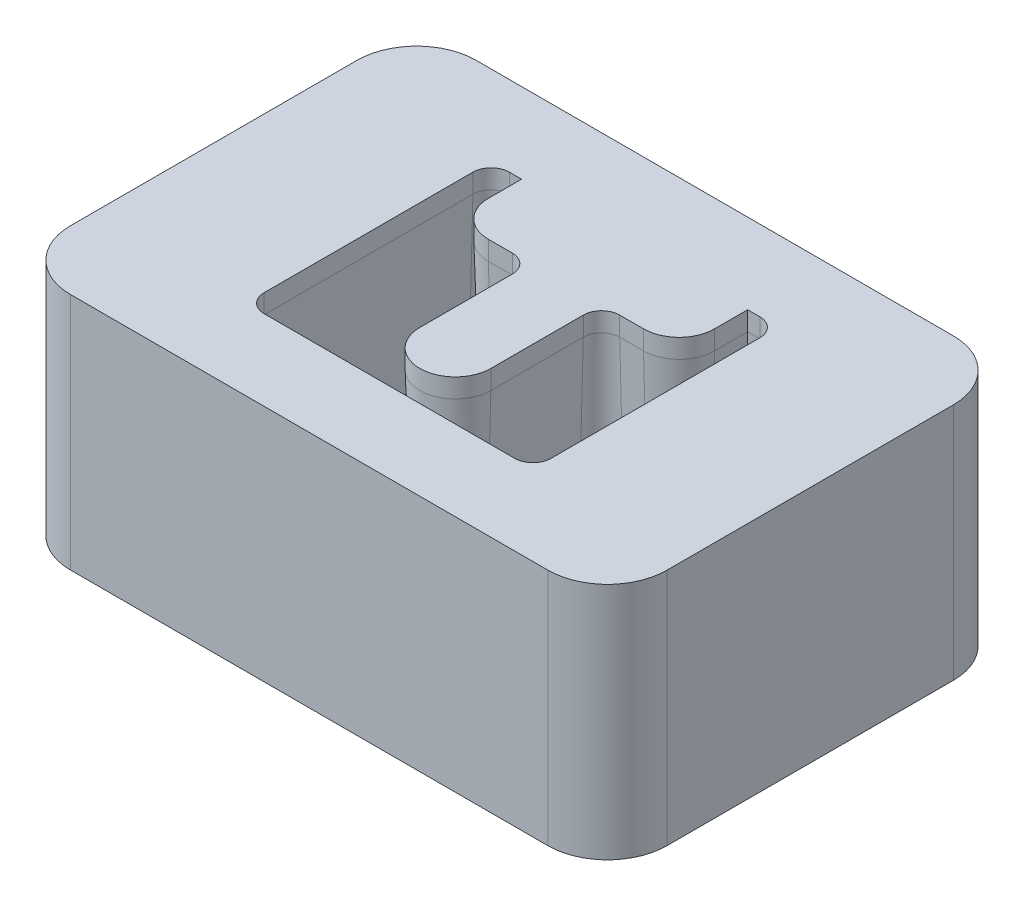
SolidWorks part; units mm, degrees
material "K110"
ref_plane "Front Plane" through (0, 0, 0) normal (0, 0, 1) x (1, 0, 0)
ref_plane "Top Plane" through (0, 0, 0) normal (0, 1, 0) x (1, 0, 0)
ref_plane "Right Plane" through (0, 0, 0) normal (1, 0, 0) x (0, 0, -1)
sketch "Sketch1" plane through (0, 0, 0) normal (0, 1, 0) x (1, 0, 0)
  line L1 (-50, -34) -> (50, -34)
  line L2 (-50, -34) -> (-50, 34)
  line L3 (-50, 34) -> (50, 34)
  line L4 (50, -34) -> (50, 34)
  line L5 (-50, -34) -> (50, 34) construction
  line L6 (-50, 34) -> (50, -34) construction
  point P0 (0, 0)
  dimension "D1" = 68
  dimension "D2" = 100
extrude "Boss-Extrude1" add sketch "Sketch1" against normal blind 40
fillet "Fillet1" radius 10 4 edges at (-50, -20, -34) (50, -20, -34) (50, -20, 34) (-50, -20, 34)
sketch "Sketch2" plane through (0, 0, 0) normal (0, 1, 0) x (1, 0, 0)
  line L22 (-21, -20.55) -> (21, -20.55)
  line L23 (-24.05, 17.5) -> (-24.05, -17.5)
  line L24 (-18.95, 20.55) -> (-21, 20.55)
  line L25 (-18.95, 15) -> (-18.95, 20.55)
  line L26 (-9, 9.05) -> (-13, 9.05)
  line L27 (-5.95, -9.5) -> (-5.95, 6)
  line L28 (5.95, 6) -> (5.95, -9.5)
  line L29 (13, 9.05) -> (9, 9.05)
  line L30 (18.95, 20.55) -> (18.95, 15)
  line L31 (21, 20.55) -> (18.95, 20.55)
  line L32 (24.05, -17.5) -> (24.05, 17.5)
  line L33 (-21, -20.55) -> (21, -20.55)
  line L34 (-24.05, 17.5) -> (-24.05, -17.5)
  line L35 (-18.95, 20.55) -> (-21, 20.55)
  line L36 (-18.95, 15) -> (-18.95, 20.55)
  line L37 (-9, 9.05) -> (-13, 9.05)
  line L38 (-5.95, -9.5) -> (-5.95, 6)
  line L39 (5.95, 6) -> (5.95, -9.5)
  line L40 (13, 9.05) -> (9, 9.05)
  line L41 (18.95, 20.55) -> (18.95, 15)
  line L42 (21, 20.55) -> (18.95, 20.55)
  line L43 (24.05, -17.5) -> (24.05, 17.5)
  arc A18 (21, -20.55) -> (24.05, -17.5) centre (21, -17.5) ccw
  arc A19 (-24.05, -17.5) -> (-21, -20.55) centre (-21, -17.5) ccw
  arc A20 (-21, 20.55) -> (-24.05, 17.5) centre (-21, 17.5) ccw
  arc A21 (-18.95, 15) -> (-13, 9.05) centre (-13, 15) ccw
  arc A22 (-5.95, 6) -> (-9, 9.05) centre (-9, 6) ccw
  arc A23 (-5.95, -9.5) -> (5.95, -9.5) centre (0, -9.5) ccw
  arc A24 (9, 9.05) -> (5.95, 6) centre (9, 6) ccw
  arc A25 (13, 9.05) -> (18.95, 15) centre (13, 15) ccw
  arc A26 (24.05, 17.5) -> (21, 20.55) centre (21, 17.5) ccw
  arc A27 (21, -20.55) -> (24.05, -17.5) centre (21, -17.5) ccw
  arc A28 (-24.05, -17.5) -> (-21, -20.55) centre (-21, -17.5) ccw
  arc A29 (-21, 20.55) -> (-24.05, 17.5) centre (-21, 17.5) ccw
  arc A30 (-18.95, 15) -> (-13, 9.05) centre (-13, 15) ccw
  arc A31 (-5.95, 6) -> (-9, 9.05) centre (-9, 6) ccw
  arc A32 (-5.95, -9.5) -> (5.95, -9.5) centre (0, -9.5) ccw
  arc A33 (9, 9.05) -> (5.95, 6) centre (9, 6) ccw
  arc A34 (13, 9.05) -> (18.95, 15) centre (13, 15) ccw
  arc A35 (24.05, 17.5) -> (21, 20.55) centre (21, 17.5) ccw
  dimension "D1" = 0.05
extrude "Cut-Extrude1" cut sketch "Sketch2" against normal up to next
sketch "Sketch3" plane through (0, 0, 0) normal (0, 0, 1) x (1, 0, 0)
  line L6 (24.05, -3.2) -> (25.0136, -40)
  line L7 (40, -40) -> (40, 0) construction
  line L8 (40, -40) -> (50, -40) construction
  line L11 (37.4, 0) -> (-37.4, 0) construction
  line L12 (25.0136, -40) -> (23.05, -40)
  line L13 (-40, -40) -> (40, -40) construction
  line L14 (23.05, -3.2) -> (24.05, -3.2)
  line L15 (23.05, -40) -> (23.05, -3.2)
  line L16 (24.05, -40) -> (24.05, 0) construction
  dimension "D1" = 3.2
  dimension "D2" = 1.5
  dimension "D3" = 1
sketch "Sketch5" plane through (0, 0, 0) normal (0, 1, 0) x (1, 0, 0)
  line L0 (21, 20.55) -> (18.95, 20.55) construction
  line L1 (24.05, -17.5) -> (24.05, 17.5) construction
  line L2 (18.95, 20.55) -> (18.95, 15) construction
  line L3 (13, 9.05) -> (9, 9.05) construction
  line L4 (5.95, 6) -> (5.95, -9.5) construction
  line L5 (-5.95, -9.5) -> (-5.95, 6) construction
  line L6 (-9, 9.05) -> (-13, 9.05) construction
  line L7 (-18.95, 15) -> (-18.95, 20.55) construction
  line L8 (-18.95, 20.55) -> (-21, 20.55) construction
  line L9 (-24.05, 17.5) -> (-24.05, -17.5) construction
  line L10 (-21, -20.55) -> (21, -20.55) construction
  line L11 (-21, -20.55) -> (21, -20.55)
  line L12 (-24.05, 17.5) -> (-24.05, -17.5)
  line L13 (-18.95, 20.55) -> (-21, 20.55)
  line L14 (-18.95, 15) -> (-18.95, 20.55)
  line L15 (-9, 9.05) -> (-13, 9.05)
  line L16 (-5.95, -9.5) -> (-5.95, 6)
  line L17 (5.95, 6) -> (5.95, -9.5)
  line L18 (13, 9.05) -> (9, 9.05)
  line L19 (18.95, 20.55) -> (18.95, 15)
  line L20 (24.05, -17.5) -> (24.05, 17.5)
  line L21 (21, 20.55) -> (18.95, 20.55)
  arc A0 (-5.95, 6) -> (-9, 9.05) centre (-9, 6) ccw construction
  arc A1 (24.05, 17.5) -> (21, 20.55) centre (21, 17.5) ccw construction
  arc A2 (13, 9.05) -> (18.95, 15) centre (13, 15) ccw construction
  arc A3 (9, 9.05) -> (5.95, 6) centre (9, 6) ccw construction
  arc A4 (-5.95, -9.5) -> (5.95, -9.5) centre (0, -9.5) ccw construction
  arc A5 (-18.95, 15) -> (-13, 9.05) centre (-13, 15) ccw construction
  arc A6 (-21, 20.55) -> (-24.05, 17.5) centre (-21, 17.5) ccw construction
  arc A7 (-24.05, -17.5) -> (-21, -20.55) centre (-21, -17.5) ccw construction
  arc A8 (21, -20.55) -> (24.05, -17.5) centre (21, -17.5) ccw construction
  arc A9 (21, -20.55) -> (24.05, -17.5) centre (21, -17.5) ccw
  arc A10 (-24.05, -17.5) -> (-21, -20.55) centre (-21, -17.5) ccw
  arc A11 (-21, 20.55) -> (-24.05, 17.5) centre (-21, 17.5) ccw
  arc A12 (-18.95, 15) -> (-13, 9.05) centre (-13, 15) ccw
  arc A13 (-5.95, 6) -> (-9, 9.05) centre (-9, 6) ccw
  arc A14 (-5.95, -9.5) -> (5.95, -9.5) centre (0, -9.5) ccw
  arc A15 (9, 9.05) -> (5.95, 6) centre (9, 6) ccw
  arc A16 (13, 9.05) -> (18.95, 15) centre (13, 15) ccw
  arc A17 (24.05, 17.5) -> (21, 20.55) centre (21, 17.5) ccw
sweep "Cut-Sweep1" cut profiles "Sketch3" path "Sketch5"
hole_wizard "M6 Tapped Hole1" positions "Sketch11" profile "Sketch9" tap size "M6" standard "ISO"
sketch "Sketch11" plane through (0, -40, 0) normal (0, -1, 0) x (-1, 0, 0)
  line L0 (-40, 34) -> (40, 34) construction
  line L1 (-50, -24) -> (-50, 24) construction
  line L2 (50, 24) -> (50, -24) construction
  line L3 (40, -34) -> (-40, -34) construction
  point P0 (-43, 27)
  point P2 (43, 27)
  point P4 (43, -27)
  point P6 (-43, -27)
  dimension "D1" = 7
  dimension "D2" = 7
  dimension "D3" = 7
  dimension "D4" = 7
sketch "Sketch9" plane through (43, -40, -27) normal (1, 0, 0) x (0, 0, -1)
  line L0 (0, 0) -> (0, 18.5022)
  line L1 (0, 18.5022) -> (2.5, 17)
  line L2 (2.5, 17) -> (2.5, 0.525)
  line L3 (2.5, 0.525) -> (3.025, 0)
  line L5 (3.025, 0) -> (0, 0)
  line L6 (-2.5, 0.525) -> (-3.025, 0) construction
  line L10 (0, 18.5022) -> (-2.5, 17) construction
  line L11 (0, -6.35) -> (0, 107.95) construction
  dimension "Tap Drill Dia." = 5
  dimension "Tap Drill Depth" = 17
  dimension "Near C'Sink Dia." = 6.05
  dimension "Near C'Sink Angle" = 90
  dimension "Drill Angle" = 118
cosmetic thread "Hole Thread1"
cosmetic thread "Hole Thread2"
cosmetic thread "Hole Thread3"
cosmetic thread "Hole Thread4"
